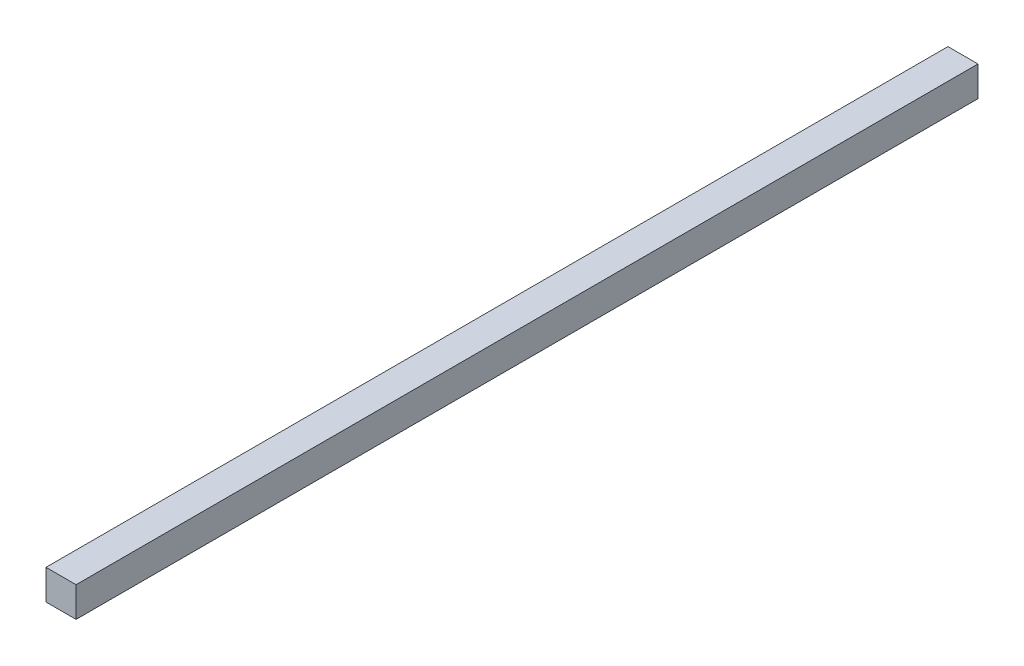
SolidWorks part; units mm, degrees
material "PTFE (general)"
ref_plane "Front Plane" through (0, 0, 0) normal (0, 0, 1) x (1, 0, 0)
ref_plane "Top Plane" through (0, 0, 0) normal (0, 1, 0) x (1, 0, 0)
ref_plane "Right Plane" through (0, 0, 0) normal (1, 0, 0) x (0, 0, -1)
sketch "Sketch1" plane through (0, 0, 0) normal (0, 0, 1) x (1, 0, 0)
  line L1 (0, 0) -> (6.35, 0)
  line L2 (0, 0) -> (0, 6.35)
  line L3 (0, 6.35) -> (6.35, 6.35)
  line L4 (6.35, 0) -> (6.35, 6.35)
  dimension "D1" = 6.35
  dimension "D2" = 6.35
extrude "Boss-Extrude1" add sketch "Sketch1" along normal blind 190.5
